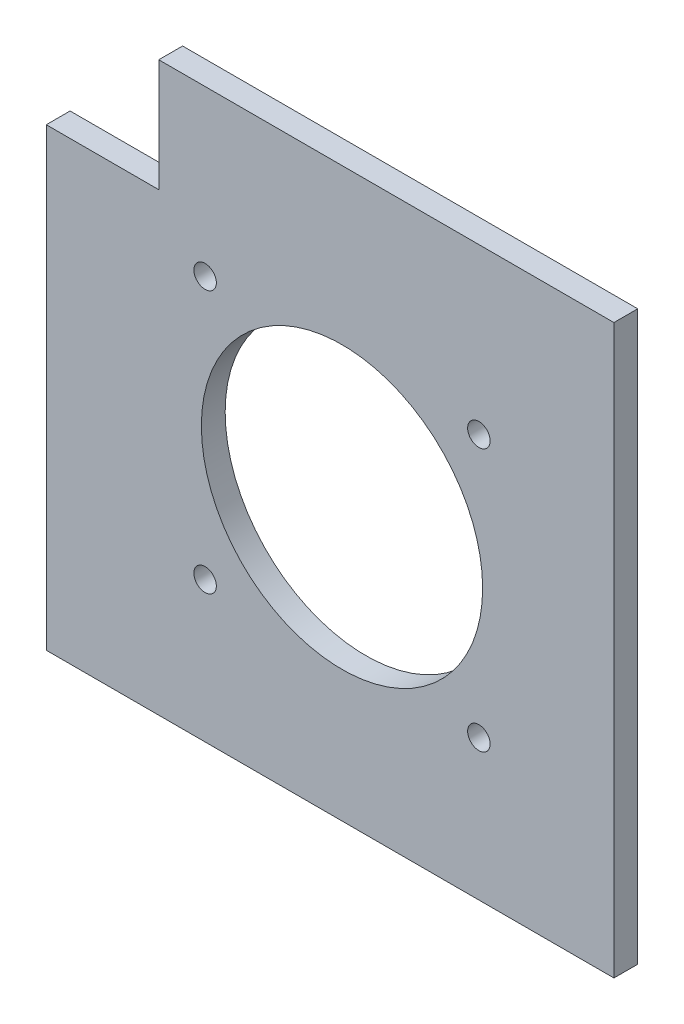
SolidWorks part; units mm, degrees
ref_plane "Alzado" through (0, 0, 0) normal (0, 0, 1) x (1, 0, 0)
ref_plane "Planta" through (0, 0, 0) normal (0, 1, 0) x (1, 0, 0)
ref_plane "Vista lateral" through (0, 0, 0) normal (1, 0, 0) x (0, 0, -1)
sketch "Croquis1" plane through (0, 0, 0) normal (0, 0, 1) x (1, 0, 0)
  line L0 (-20.3565, 25.4833) -> (100.9935, 25.4833) construction
  line L7 (100.9935, 25.4833) -> (100.9935, -125.8667) construction
  line L8 (100.9935, -125.8667) -> (-50.3565, -125.8667) construction
  line L9 (-50.3565, -125.8667) -> (-50.3565, -4.5167) construction
  line L10 (-50.3565, -4.5167) -> (-50.3565, -125.8667)
  line L11 (-50.3565, -4.5167) -> (-20.3565, -4.5167)
  line L12 (-20.3565, 25.4833) -> (-20.3565, -4.5167)
  line L13 (-50.3565, -125.8667) -> (100.9935, -125.8667)
  line L14 (100.9935, -125.8667) -> (100.9935, 25.4833)
  line L15 (100.9935, 25.4833) -> (-20.3565, 25.4833)
  point P0 (0, 0)
extrude "Saliente-Extruir1" add sketch "Croquis1" along normal blind 6.35
sketch "Croquis2" plane through (0, 0, 6.35) normal (0, 0, 1) x (1, 0, 0)
  line L0 (-50.3565, -10.8667) -> (-14.0065, -10.8667) construction
  line L1 (-50.3565, -4.5167) -> (-50.3565, -125.8667) construction
  line L2 (-14.0065, -10.8667) -> (70.9935, -95.8667) construction
  line L7 (-14.0065, -10.8667) -> (-14.0065, -18.3667) construction
  line L8 (-14.0065, -18.3667) -> (-8.0065, -18.3667) construction
  line L9 (-14.0065, -95.8667) -> (-14.0065, -88.3667) construction
  line L10 (-14.0065, -88.3667) -> (-8.0065, -88.3667) construction
  line L11 (28.4935, -95.8667) -> (28.4935, -73.1293) construction
  circle A0 centre (28.4935, -53.3667) radius 37.5
  circle A1 centre (-8.0065, -18.3667) radius 3
  circle A2 centre (-8.0065, -88.3667) radius 3
  circle A3 centre (64.9935, -18.3667) radius 3
  circle A4 centre (64.9935, -88.3667) radius 3
  dimension "D5" = 75
  dimension "D10" = 6
  dimension "D11" = 6
  dimension "D1" = 6.35
  dimension "D2" = 6.35
  dimension "D3" = 85
  dimension "D4" = 85
  dimension "D6" = 7.5
  dimension "D7" = 6
  dimension "D8" = 6
  dimension "D9" = 7.5
extrude "Cortar-Extruir1" cut sketch "Croquis2" against normal blind 6.35
